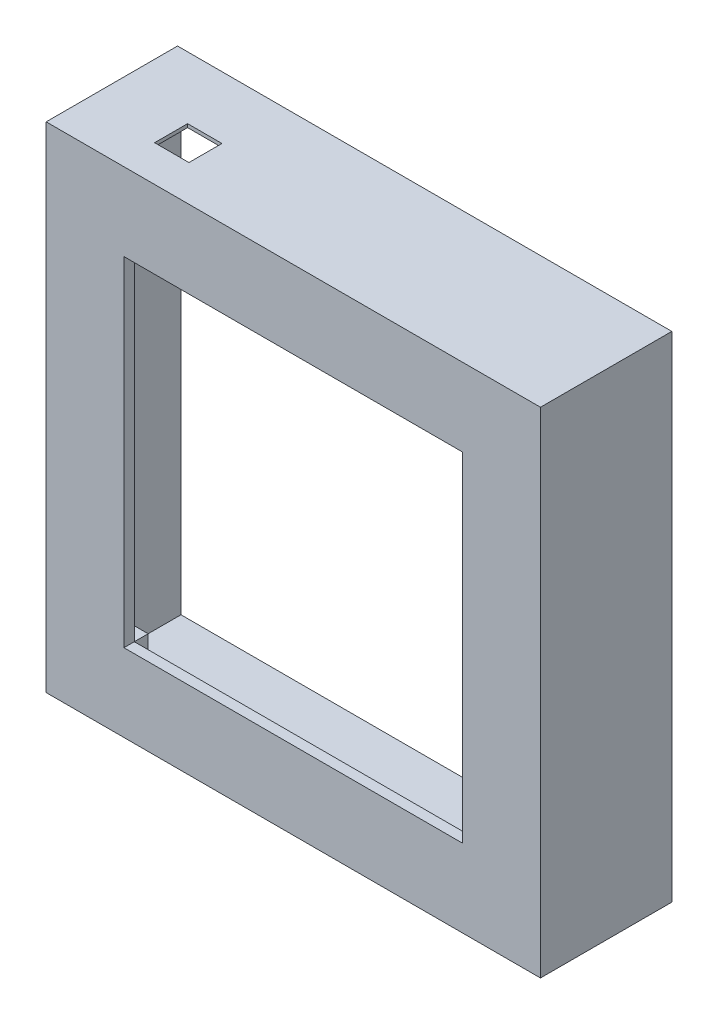
SolidWorks part; units mm, degrees
ref_plane "Front Plane" through (0, 0, 0) normal (0, 0, 1) x (1, 0, 0)
ref_plane "Top Plane" through (0, 0, 0) normal (0, 1, 0) x (1, 0, 0)
ref_plane "Right Plane" through (0, 0, 0) normal (1, 0, 0) x (0, 0, -1)
sketch "Sketch1" plane through (0, 0, 0) normal (0, 0, 1) x (1, 0, 0)
  line L1 (-49, -49) -> (49, -49)
  line L2 (-49, -49) -> (-49, 49)
  line L3 (-49, 49) -> (49, 49)
  line L4 (49, -49) -> (49, 49)
  line L5 (-49, -49) -> (49, 49) construction
  line L6 (-49, 49) -> (49, -49) construction
  line L7 (-71.5, -71.5) -> (71.5, -71.5)
  line L8 (-71.5, -71.5) -> (-71.5, 71.5)
  line L9 (-71.5, 71.5) -> (71.5, 71.5)
  line L10 (71.5, -71.5) -> (71.5, 71.5)
  line L11 (-71.5, -71.5) -> (71.5, 71.5) construction
  line L12 (-71.5, 71.5) -> (71.5, -71.5) construction
  point P0 (0, 0)
  point P6 (0, 0)
extrude "Boss-Extrude1" add sketch "Sketch1" along normal blind 3
sketch "Sketch2" plane through (0, 0, 0) normal (0, 0, -1) x (-1, 0, 0)
  line L1 (-71.5, -71.5) -> (71.5, -71.5)
  line L2 (-71.5, -71.5) -> (-71.5, 71.5)
  line L3 (-71.5, 71.5) -> (71.5, 71.5)
  line L4 (71.5, -71.5) -> (71.5, 71.5)
  line L5 (-71.5, -71.5) -> (71.5, 71.5) construction
  line L6 (-71.5, 71.5) -> (71.5, -71.5) construction
  line L7 (-70.5, -70.5) -> (70.5, -70.5)
  line L8 (-70.5, -70.5) -> (-70.5, 70.5)
  line L9 (-70.5, 70.5) -> (70.5, 70.5)
  line L10 (70.5, -70.5) -> (70.5, 70.5)
  line L11 (-70.5, -70.5) -> (70.5, 70.5) construction
  line L12 (-70.5, 70.5) -> (70.5, -70.5) construction
  point P0 (0, 0)
  point P7 (0, 0)
extrude "Boss-Extrude2" add sketch "Sketch2" along normal blind 35
sketch "Sketch3" plane through (0, 0, 0) normal (0, 0, -1) x (-1, 0, 0)
  line L1 (-70.5, 70.5) -> (-49, 70.5)
  line L2 (-70.5, 70.5) -> (-70.5, 49)
  line L3 (-70.5, 49) -> (-49, 49)
  line L4 (-49, 70.5) -> (-49, 49)
  line L5 (-70.5, -70.5) -> (-49, -70.5)
  line L6 (-70.5, -70.5) -> (-70.5, -49)
  line L7 (-70.5, -49) -> (-49, -49)
  line L8 (-49, -70.5) -> (-49, -49)
  line L9 (70.5, -70.5) -> (49, -70.5)
  line L10 (70.5, -70.5) -> (70.5, -49)
  line L11 (70.5, -49) -> (49, -49)
  line L12 (49, -70.5) -> (49, -49)
  line L13 (70.5, 70.5) -> (49, 70.5)
  line L14 (70.5, 70.5) -> (70.5, 49)
  line L15 (70.5, 49) -> (49, 49)
  line L16 (49, 70.5) -> (49, 49)
extrude "Boss-Extrude3" add sketch "Sketch3" along normal blind 4
sketch "Sketch4" plane through (0, 71.5, 0) normal (0, 1, 0) x (1, 0, 0)
  line L1 (-50.5885, 7.454) -> (-40.6514, 7.454)
  line L2 (-50.5885, 7.454) -> (-50.5885, 17.0039)
  line L3 (-50.5885, 17.0039) -> (-40.6514, 17.0039)
  line L4 (-40.6514, 7.454) -> (-40.6514, 17.0039)
extrude "Cut-Extrude1" cut sketch "Sketch4" against normal blind 4
